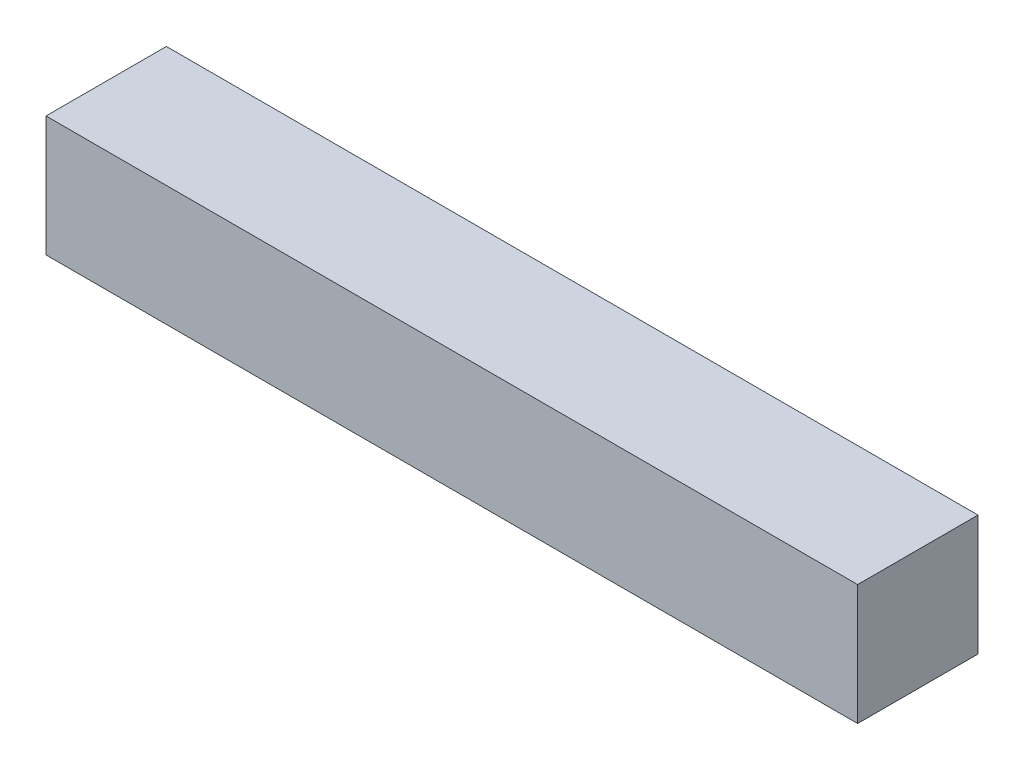
SolidWorks part; units mm, degrees
ref_plane "Front Plane" through (0, 0, 0) normal (0, 0, 1) x (1, 0, 0)
ref_plane "Top Plane" through (0, 0, 0) normal (0, 1, 0) x (1, 0, 0)
ref_plane "Right Plane" through (0, 0, 0) normal (1, 0, 0) x (0, 0, -1)
sketch "Sketch1" plane through (0, 0, 0) normal (0, 1, 0) x (1, 0, 0)
  line L1 (0, 0) -> (5.9, 0)
  line L2 (0, 0) -> (0, -0.875)
  line L3 (0, -0.875) -> (5.9, -0.875)
  line L4 (5.9, 0) -> (5.9, -0.875)
  dimension "D1" = 5.9
  dimension "D2" = 0.875
extrude "Boss-Extrude3" add sketch "Sketch1" along normal blind 0.875
